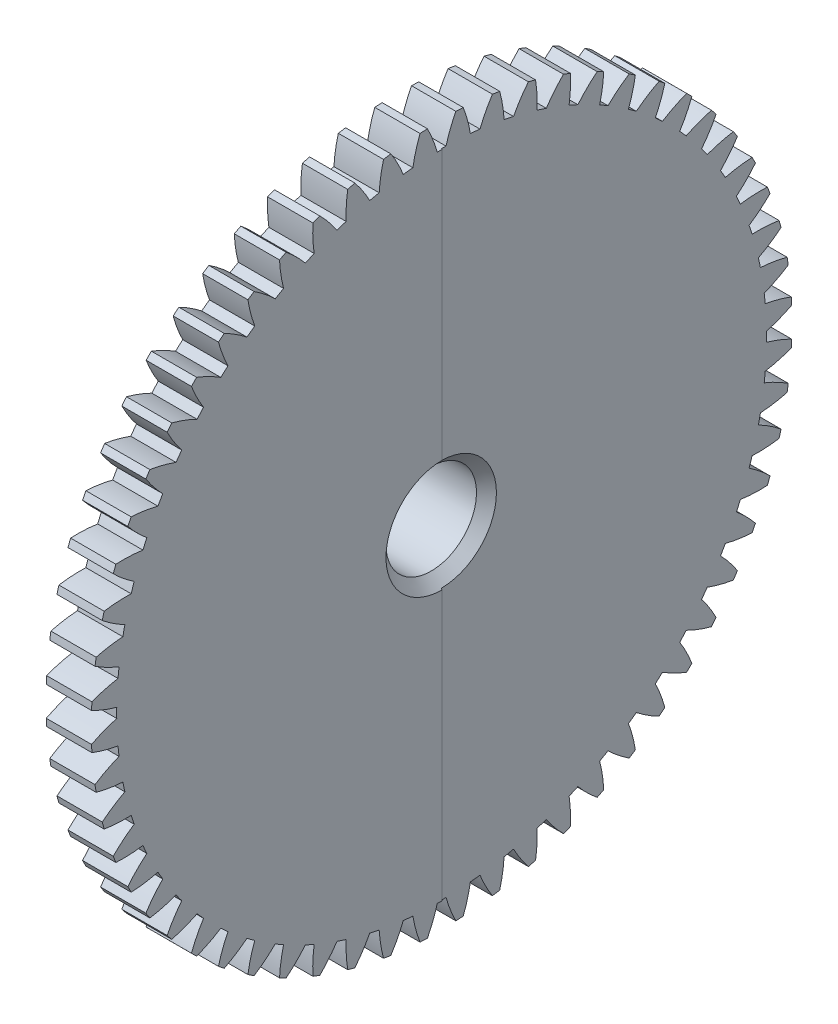
SolidWorks part; units mm, degrees
material "Delrin 2700 NC010, Low Viscosity Acetal Copolymer (SS)"
ref_plane "Plane1" through (0, 0, 0) normal (0, 0, 1) x (1, 0, 0)
ref_plane "Plane2" through (0, 0, 0) normal (0, 1, 0) x (1, 0, 0)
ref_plane "Plane3" through (0, 0, 0) normal (1, 0, 0) x (0, 0, -1)
sketch "HoldingSke" plane through (0, 0, 0) normal (0, 1, 0) x (1, 0, 0)
  line L0 (0, 0) -> (203.2, -351.9527)
  line L1 (-15, 0) -> (100, 0) construction
  line L2 (0, 0) -> (-2.1039, 2.3779)
  line L3 (0, 0) -> (-11.863, 4.5341)
  line L4 (0, 0) -> (4.318, 7.479)
  line L5 (0, 0) -> (-23.7986, -8.8762)
  line L6 (0, 0) -> (-5.2639, -3.5516)
  line L7 (-2.1039, 2.3779) -> (3.3635, 27.1825)
  line L8 (-76.2, 54.61) -> (-61.976, 54.61)
  line L9 (-71.009, 38.7566) -> (-53.1078, 45.2721)
  line L10 (-76.2, 71.12) -> (104.1128, 71.12)
  line L11 (0, 0) -> (-6.35, 0)
  line L12 (-76.2, 101.6) -> (-76.1428, 101.6)
  line L13 (24.9733, 27.94) -> (52.9518, 28.4284)
  line L14 (24.9733, 27.94) -> (24.9746, 27.94)
  line L15 (24.9733, 27.94) -> (100.4006, 29.5858)
  circle A0 centre (0, 0) radius 6.35
  circle A1 centre (0, 0) radius 15.875
  circle A2 centre (0, 0) radius 15.875
  circle A3 centre (0, 0) radius 6.35
  dimension "MHD" = 31.75
  dimension "Hub_dia" = 31.75
  dimension "Bore" = 12.7
  dimension "MBD" = 12.7
  dimension "Num_teeth" = 60
  dimension "Pitch_radius" = 180.3128
  dimension "Pitch" = 406.4
  dimension "Width" = 6.35
  dimension "Overall_len" = 25.4
  dimension "Show_teeth" = 60
  dimension "Thickness" = 6.35
  dimension "OAL" = 25.4001
  dimension "T_dim" = 14.224
  dimension "Ap" = 20
  dimension "H" = 19.05
  dimension "Backlash" = 0.0571
  dimension "Addendum_fac" = 1
  dimension "Dedendum_fac" = 1.25
  dimension "Clearance_fac" = 0.25
  dimension "Dedendum_add" = 0.0013
sketch "BasProSke" plane through (0, 0, 0) normal (0, 1, 0) x (1, 0, 0)
  line L0 (-10, 0) -> (60, 0) construction
  line L1 (0, 0) -> (0, 49.2125)
  line L2 (0, 0) -> (6.35, 0)
  line L3 (6.35, 0) -> (6.35, 49.2125)
  line L4 (6.35, 49.2125) -> (0, 49.2125)
  dimension "Diameter" = 98.425
  dimension "Thickness" = 6.35
revolve "Base-Revolve" add sketch "BasProSke" angle 360 about L0
sketch "TooCutSke" plane through (0, 0, 0) normal (1, 0, 0) x (0, 0, -1)
  line L1 (0, 0) -> (0, 107) construction
  line L2 (0, 0) -> (-1.3467, 47.606) construction
  line L3 (0, 0) -> (-4.9836, 95.0919) construction
  line L4 (-1.3467, 47.606) -> (-2.4918, 47.5459) construction
  arc A0 (0.6776, 45.6343) -> (-0.6776, 45.6343) centre (0, 0) ccw
  arc A1 (2.0706, 49.1943) -> (-2.0706, 49.1943) centre (0, 0) ccw
  circle A2 centre (0, 0) radius 47.625 construction
  circle A3 centre (0, 0) radius 44.7529 construction
  arc A4 (-0.6776, 45.6343) -> (-2.0706, 49.1943) centre (-19.0248, 40.5077) ccw
  arc A5 (2.0706, 49.1943) -> (0.6776, 45.6343) centre (19.0248, 40.5077) ccw
  dimension "Root_dia" = 91.2787
  dimension "Overcut_dia" = 98.4758
  dimension "Pitch_dia" = 95.25
  dimension "Base_dia" = 89.5057
  dimension "Flank_rad" = 19.05
  dimension "Half_ang" = 3
  dimension "Half_CT" = 1.1467
extrude "ToothCut" cut sketch "TooCutSke" along normal through all
fillet "Breaks" [suppressed] radius 0.0318
fillet "RootFillets" [suppressed] radius 0.3981
pattern_circular "TeethCuts" count 60 every 6 about axis through (-10, 0, 0) along (1, 0, 0) of "ToothCut", "RootFillets", "Breaks"
sketch "HubNeaOneSke" plane through (0, 0, 0) normal (-1, 0, 0) x (0, 0, 1)
  circle A0 centre (0, 0) radius 15.875
  dimension "Diameter" = 31.75
extrude "HubNearOne" add sketch "HubNeaOneSke" along normal blind 19.0501
sketch "HubNeaBotSke" plane through (0, 0, 0) normal (-1, 0, 0) x (0, 0, 1)
  circle A0 centre (0, 0) radius 15.875
  dimension "Diameter" = 31.75
extrude "HubNearBoth" [suppressed] add sketch "HubNeaBotSke" along normal blind 9.525
ref_plane "FarPln" through (6.35, 0, 0) normal (1, 0, 0) x (0, 0, -1)
sketch "HubFarSke" plane through (6.35, 0, 0) normal (1, 0, 0) x (0, 0, -1)
  circle A0 centre (0, 0) radius 15.875
  dimension "Diameter" = 31.75
extrude "HubFar" [suppressed] add sketch "HubFarSke" along normal blind 9.525
sketch "BorSke" plane through (0, 0, 0) normal (1, 0, 0) x (0, 0, -1)
  circle A0 centre (0, 0) radius 6.35
  dimension "Diameter" = 12.7
extrude "Bore" cut sketch "BorSke" along normal mid plane 50.8001
sketch "KeySke" plane through (0, 0, 0) normal (1, 0, 0) x (0, 0, -1)
  line L0 (-1.5875, 0) -> (-1.5875, 7.874)
  line L1 (-1.5875, 7.874) -> (1.5875, 7.874)
  line L2 (1.5875, 7.874) -> (1.5875, 0)
  line L3 (0, 0) -> (0, 34) construction
  line L4 (-1.5875, 0) -> (1.5875, 0)
  dimension "Offset" = 7.874
  dimension "Width" = 3.175
extrude "Keyway" [suppressed] cut sketch "KeySke" along normal mid plane 50.8001
pattern_circular "Keyway2" [suppressed] count 2 every 90 about axis through (-10, 0, 0) along (1, 0, 0)
fillet "Fillet1" radius 1.524 2 edges at (0, 0, -15.875) (-19.0501, 0, 15.875)
chamfer "Chamfer1" distance 1.524 angle 45 2 edges at (-19.0501, 0, 6.35) (6.35, 0, 6.35)
sketch "Sketch1" plane through (0, 0, 0) normal (0, 0, 1) x (1, 0, 0)
  line L0 (-17.5261, 0) -> (-1.524, 0) construction
  line L1 (-17.5261, -15.875) -> (-17.5261, 15.875) construction
  line L2 (-1.524, -15.875) -> (-1.524, 15.875) construction
  circle A0 centre (-9.525, 0) radius 2.3813
  dimension "D1" = 4.7625
extrude "Cut-Extrude1" cut sketch "Sketch1" against normal through all and the other way through all
sketch "Sketch2" plane through (6.35, 0, 0) normal (1, 0, 0) x (0, 0, -1)
  line L0 (0, -56.6274) -> (0, 58.6462)
  line L1 (0, 58.6462) -> (52.5898, 58.6462)
  line L2 (52.5898, 58.6462) -> (52.5898, -56.6274)
  line L3 (52.5898, -56.6274) -> (0, -56.6274)
  dimension "D1" = 52.5898
  dimension "D2" = 115.2736
  dimension "D3" = 58.6462
extrude "Cut-Extrude2" cut sketch "Sketch2" against normal blind 0.127
equation "' \"Pitch@HoldingSke\" = 4"
equation "' \"Num_teeth@HoldingSke\" = 12"
equation "' \"Ap@HoldingSke\" =  20"
equation "' \"Width@HoldingSke\" = 0.5"
equation "' \"Hub_dia@HoldingSke\"= 1"
equation "' \"Overall_len@HoldingSke\" = 1.0"
equation "' \"Bore@HoldingSke\" = 0.75"
equation "' \"T_dim@HoldingSke\" = 0.85"
equation "' \"Width@KeySke\" = 0.25"
equation "' \"Show_teeth@HoldingSke\" = 13"
equation "' \"Backlash@HoldingSke\" = 0.009"
equation "' \"Addendum_fac@HoldingSke\" = 1.0"
equation "' \"Dedendum_fac@HoldingSke\" = 1.25"
equation "' \"Dedendum_add@HoldingSke\" = 0.00005"
equation "' \"Clearance_fac@HoldingSke\" = 0.25"
equation "' \"Pitch@HoldingSke\" = 0.5"
equation "' \"Num_teeth@HoldingSke\" = 23"
equation "' \"Show_teeth@HoldingSke\" = 23"
equation "' \"Backlash@HoldingSke\" = 0.0375"
equation "\"Overcut_dia@TooCutSke\" = (\"Num_teeth@HoldingSke\" + 2 * \"Addendum_fac@HoldingSke\") / \"Pitch@HoldingSke\" + 0.002"
equation "\"Pitch_dia@TooCutSke\" = \"Num_teeth@HoldingSke\" / \"Pitch@HoldingSke\""
equation "\"Base_dia@TooCutSke\" = \"Num_teeth@HoldingSke\" / \"Pitch@HoldingSke\" * cos((\"Ap@HoldingSke\"  * 3.14159265 / 180))"
equation "\"Root_dia@TooCutSke\" = (\"Num_teeth@HoldingSke\" + 2) / \"Pitch@HoldingSke\" - 2 * (\"Addendum_fac@HoldingSke\" + \"Dedendum_fac@HoldingSke\") / \"Pitch@HoldingSke\" - \"Dedendum_add@HoldingSke\" * 2"
equation "\"Half_ang@TooCutSke\" = 180 / \"Num_teeth@HoldingSke\""
equation "\"Half_CT@TooCutSke\" = \"Num_teeth@HoldingSke\" / \"Pitch@HoldingSke\" * sin((3.14159265 / 2 / \"Num_teeth@HoldingSke\")) / 2 - 7 * \"Backlash@HoldingSke\" / 4"
equation "\"Flank_rad@TooCutSke\" = \"Num_teeth@HoldingSke\" / \"Pitch@HoldingSke\" / 5"
equation "\"Radius@RootFillets\" = \"Clearance_fac@HoldingSke\" / \"Pitch@HoldingSke\" + \"Dedendum_add@HoldingSke\""
equation "\"Break_rad@Breaks\" = 0.02 / \"Pitch@HoldingSke\""
equation "\"Thickness@HoldingSke\" = \"Width@HoldingSke\""
equation "\"OAL@HoldingSke\" = \"Thickness@HoldingSke\""
equation "\"MHD@HoldingSke\" = (\"Num_teeth@HoldingSke\" + 2) / \"Pitch@HoldingSke\" - 2 * (\"Addendum_fac@HoldingSke\" + \"Dedendum_fac@HoldingSke\")  / \"Pitch@HoldingSke\" - \"Dedendum_add@HoldingSke\" * 2"
equation "\"MBD@HoldingSke\" = (\"Num_teeth@HoldingSke\" + 2) / \"Pitch@HoldingSke\" - 2 * (\"Addendum_fac@HoldingSke\" + \"Dedendum_fac@HoldingSke\")  / \"Pitch@HoldingSke\" - \"Dedendum_add@HoldingSke\" * 2 - 0.002"
equation "\"MHD@HoldingSke\" = ((sgn( \"MHD@HoldingSke\" - \"Hub_dia@HoldingSke\" )-1)*( \"MHD@HoldingSke\" - \"Hub_dia@HoldingSke\" ))/-2+ \"Hub_dia@HoldingSke\""
equation "\"MBD@HoldingSke\" = ((sgn( \"MBD@HoldingSke\" - \"Bore@HoldingSke\" )-1)*( \"MBD@HoldingSke\" - \"Bore@HoldingSke\" ))/-2+ \"Bore@HoldingSke\""
equation "\"OAL@HoldingSke\" = ((sgn( \"OAL@HoldingSke\" - \"Overall_len@HoldingSke\" )+1)*( \"OAL@HoldingSke\" - \"Overall_len@HoldingSke\" ))/2 + \"Overall_len@HoldingSke\" + 0.000002"
equation "\"Num_teeth@TeethCuts\" = int( \"Show_teeth@HoldingSke\" ) + 1"
equation "\"Num_teeth@TeethCuts\" = ((sgn( \"Num_teeth@TeethCuts\" - \"Num_teeth@HoldingSke\" )-1)*( \"Num_teeth@TeethCuts\" - \"Num_teeth@HoldingSke\" ))/-2+ \"Num_teeth@HoldingSke\""
equation "\"Num_teeth@TeethCuts\" = ((sgn( \"Num_teeth@TeethCuts\" - 2.0)+1)*( \"Num_teeth@TeethCuts\" - 2.0))/2 +2.0"
equation "\"Angle@TeethCuts\" = 360.0 / \"Num_teeth@HoldingSke\""
equation "\"Diameter@BasProSke\" = (\"Num_teeth@HoldingSke\" + 2 * \"Addendum_fac@HoldingSke\") / \"Pitch@HoldingSke\""
equation "\"Thickness@BasProSke\"  = \"Thickness@HoldingSke\""
equation "' \"Fillet_rad@BasProSke\" =  \"Thickness@HoldingSke\" * 0.05"
equation "\"MHD@HoldingSke\" = ((sgn( \"MHD@HoldingSke\" - \"Root_dia@TooCutSke\" )-1)*( \"MHD@HoldingSke\" - \"Root_dia@TooCutSke\" ))/-2+ \"Root_dia@TooCutSke\""
equation "\"Diameter@HubNeaOneSke\" = \"MHD@HoldingSke\""
equation "\"Length@HubNearOne\" = \"OAL@HoldingSke\" - \"Thickness@BasProSke\""
equation "\"Diameter@HubNeaBotSke\" = \"MHD@HoldingSke\""
equation "\"Length@HubNearBoth\" = ( \"OAL@HoldingSke\" - \"Thickness@BasProSke\" ) / 2.0"
equation "\"Thickness@FarPln\" = \"Thickness@BasProSke\""
equation "\"Diameter@HubFarSke\" = \"MHD@HoldingSke\""
equation "\"Length@HubFar\" = ( \"OAL@HoldingSke\" - \"Thickness@BasProSke\" ) / 2.0"
equation "\"Diameter@BorSke\" = \"MBD@HoldingSke\""
equation "\"D1@Bore\" = \"OAL@HoldingSke\" * 2.0"
equation "\"D1@Keyway\" = \"OAL@HoldingSke\" * 2.0"
equation "\"Offset@KeySke\" = \"T_dim@HoldingSke\" - \"MBD@HoldingSke\" / 2.0"
